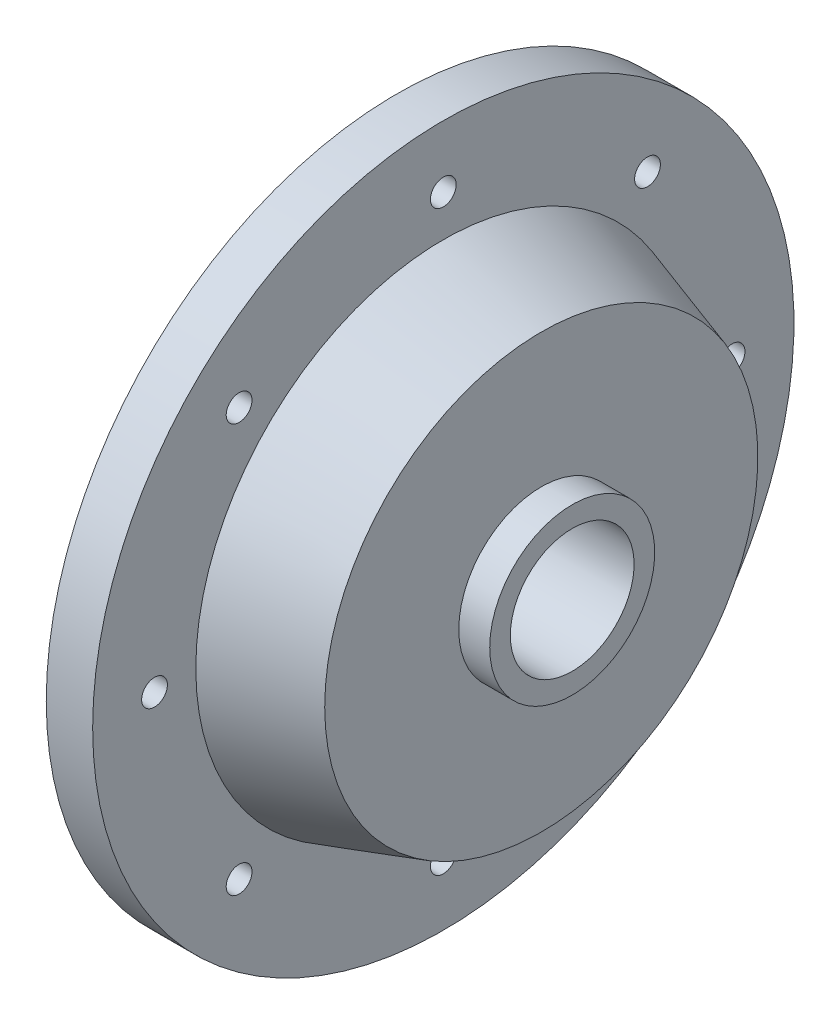
SolidWorks part; units mm, degrees
material "PE High Density"
ref_plane "Front Plane" through (0, 0, 0) normal (0, 0, 1) x (1, 0, 0)
ref_plane "Top Plane" through (0, 0, 0) normal (0, 1, 0) x (1, 0, 0)
ref_plane "Right Plane" through (0, 0, 0) normal (1, 0, 0) x (0, 0, -1)
sketch "Sketch1" plane through (0, 0, 0) normal (0, 0, 1) x (1, 0, 0)
  line L0 (0, 0) -> (59.5118, 0) construction
  line L1 (5, 12) -> (34, 12)
  line L2 (34, 12) -> (34, 16)
  line L3 (34, 16) -> (28, 16)
  line L4 (28, 16) -> (28, 42)
  line L5 (28, 42) -> (9, 48)
  line L6 (9, 48) -> (9, 68)
  line L7 (9, 68) -> (0, 68)
  line L8 (0, 68) -> (0, 64)
  line L9 (0, 64) -> (5, 64)
  line L10 (5, 64) -> (5, 40)
  line L11 (5, 40) -> (20, 40)
  line L12 (20, 40) -> (20, 16)
  line L13 (20, 16) -> (5, 16)
  line L14 (5, 16) -> (5, 12)
  point P16 (0, 66)
  dimension "D1" = 12
  dimension "D2" = 16
  dimension "D3" = 42
  dimension "D4" = 48
  dimension "D5" = 68
  dimension "D6" = 64
  dimension "D7" = 24
  dimension "D8" = 5
  dimension "D9" = 9
  dimension "D10" = 20
  dimension "D11" = 28
  dimension "D12" = 34
revolve "Revolve1" add sketch "Sketch1" angle 360 about L0
sketch "Sketch2" plane through (9, 0, 0) normal (1, 0, 0) x (0, 0, -1)
  circle A0 centre (0, 56) radius 2.5
  circle A1 centre (39.598, 39.598) radius 2.5
  circle A2 centre (56, 0) radius 2.5
  circle A3 centre (39.598, -39.598) radius 2.5
  circle A4 centre (0, -56) radius 2.5
  circle A5 centre (-39.598, -39.598) radius 2.5
  circle A6 centre (-56, 0) radius 2.5
  circle A7 centre (-39.598, 39.598) radius 2.5
  point P19 (0, 0)
  dimension "D1" = 5
  dimension "D2" = 56
  dimension "D3" = 8
extrude "Cut-Extrude1" cut sketch "Sketch2" against normal through all
